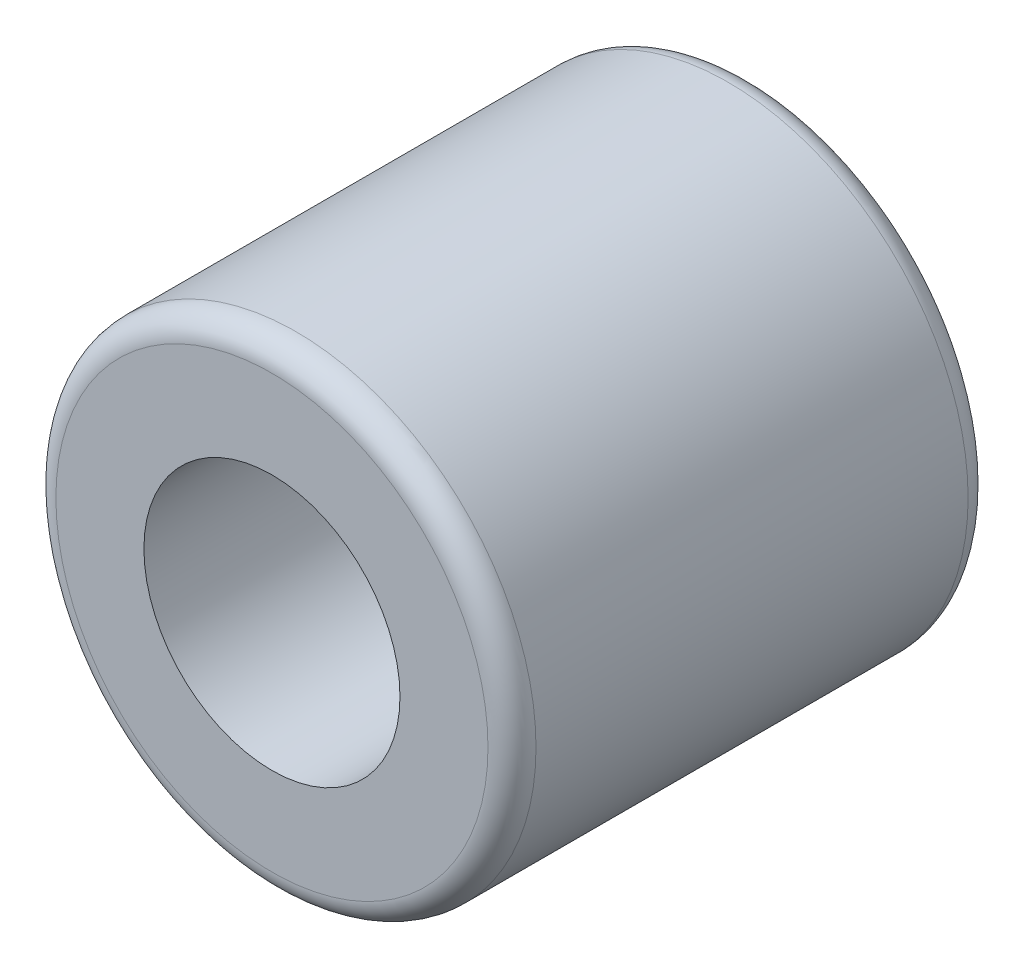
SolidWorks part; units mm, degrees
ref_plane "Front Plane" through (0, 0, 0) normal (0, 0, 1) x (1, 0, 0)
ref_plane "Top Plane" through (0, 0, 0) normal (0, 1, 0) x (1, 0, 0)
ref_plane "Right Plane" through (0, 0, 0) normal (1, 0, 0) x (0, 0, -1)
sketch "Sketch1" plane through (0, 0, 0) normal (0, 0, 1) x (1, 0, 0)
  circle A0 centre (0, 0) radius 3
  circle A1 centre (0, 0) radius 1.6
  dimension "D1" = 6
  dimension "D2" = 3.2
extrude "Boss-Extrude1" add sketch "Sketch1" along normal blind 6
fillet "Fillet1" radius 0.3 2 edges at (3, 0, 0) (3, 0, 6)
